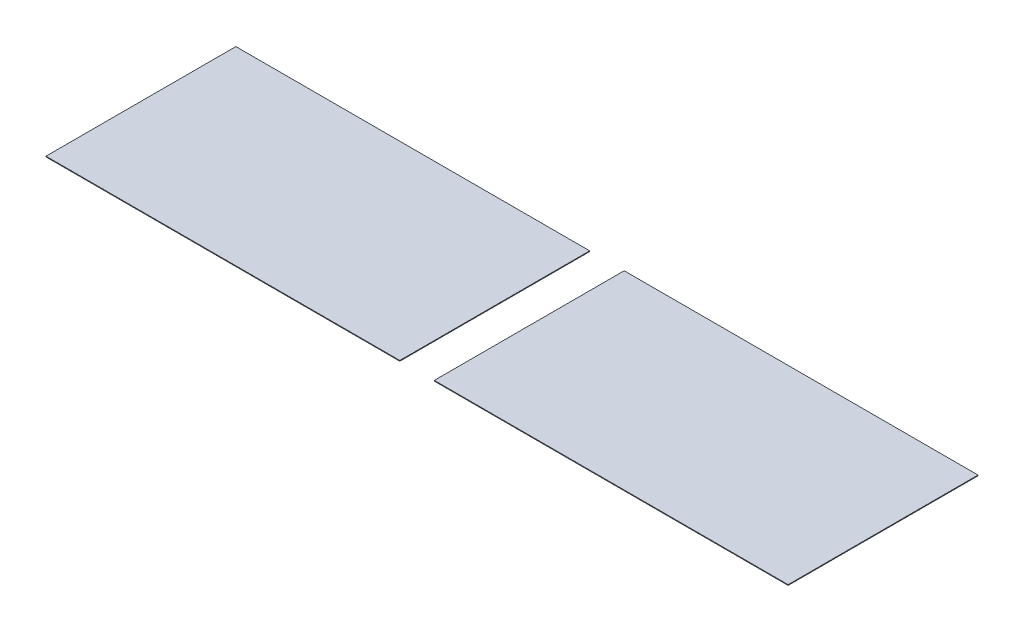
SolidWorks part; units mm, degrees
ref_plane "Спереди" through (0, 0, 0) normal (0, 0, 1) x (1, 0, 0)
ref_plane "Сверху" through (0, 0, 0) normal (0, 1, 0) x (1, 0, 0)
ref_plane "Справа" through (0, 0, 0) normal (1, 0, 0) x (0, 0, -1)
sketch "Эскиз1" plane through (0, 0, 0) normal (0, 1, 0) x (1, 0, 0)
  line L1 (0, 0) -> (20.5, 0)
  line L2 (0, 0) -> (0, 11)
  line L3 (0, 11) -> (20.5, 11)
  line L4 (20.5, 0) -> (20.5, 11)
  line L5 (22.5, 0) -> (43, 0)
  line L6 (22.5, 0) -> (22.5, 11)
  line L7 (22.5, 11) -> (43, 11)
  line L8 (43, 0) -> (43, 11)
  dimension "D1" = 20.5
  dimension "D2" = 11
  dimension "D3" = 2
  dimension "D4" = 20.5
extrude "Бобышка-Вытянуть1" add sketch "Эскиз1" along normal blind 0.04
